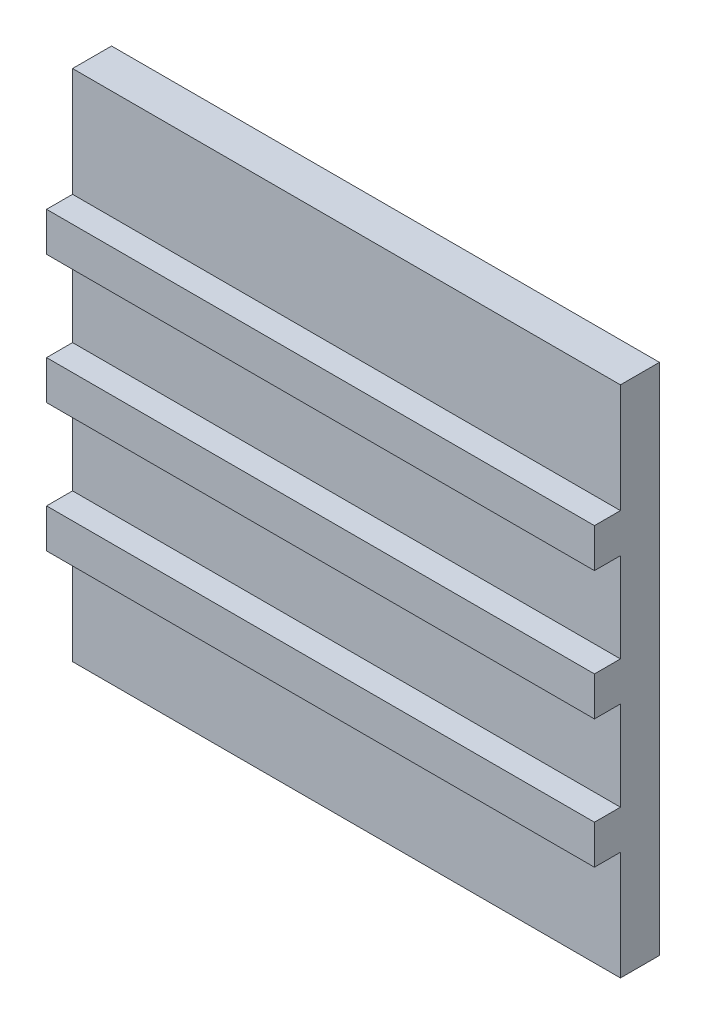
SolidWorks part; units mm, degrees
ref_plane "Front Plane" through (0, 0, 0) normal (0, 0, 1) x (1, 0, 0)
ref_plane "Top Plane" through (0, 0, 0) normal (0, 1, 0) x (1, 0, 0)
ref_plane "Right Plane" through (0, 0, 0) normal (1, 0, 0) x (0, 0, -1)
sketch "Sketch2" plane through (0, 0, 0) normal (0, 0, 1) x (1, 0, 0)
  line L1 (-51.6665, 20.5898) -> (-9.5165, 20.5898)
  line L2 (-51.6665, 20.5898) -> (-51.6665, -18.9302)
  line L3 (-51.6665, -18.9302) -> (-9.5165, -18.9302)
  line L4 (-9.5165, 20.5898) -> (-9.5165, -18.9302)
extrude "Boss-Extrude1" add sketch "Sketch2" along normal blind 3
sketch "Sketch3" plane through (0, 0, 3) normal (0, 0, 1) x (1, 0, 0)
  line L0 (-51.6665, -9.0502) -> (-51.6665, 0.8298) construction
  line L1 (-51.6665, -18.9302) -> (-51.6665, -9.0502) construction
  line L2 (-51.6665, -9.0502) -> (-9.5165, -9.0502) construction
  line L3 (-9.5165, -18.9302) -> (-9.5165, 20.5898) construction
  line L4 (-51.6665, 20.5898) -> (-51.6665, -18.9302) construction
  line L5 (-51.6665, 0.8298) -> (-51.6665, 10.7098) construction
  line L6 (-51.6665, 10.7098) -> (-9.5165, 10.7098) construction
  line L7 (-51.6665, -9.0502) -> (-51.6665, -10.5502)
  line L8 (-51.6665, -9.0502) -> (-51.6665, -7.5502)
  line L9 (-51.6665, -7.5502) -> (-9.5165, -7.5502)
  line L10 (-9.5165, -7.5502) -> (-9.5165, -10.5502)
  line L11 (-9.5165, -10.5502) -> (-51.6665, -10.5502)
  line L12 (-51.6665, 10.7098) -> (-51.6665, 12.2098)
  line L13 (-51.6665, 12.2098) -> (-9.5165, 12.2098)
  line L14 (-9.5165, 12.2098) -> (-9.5165, 9.2098)
  line L15 (-9.5165, 9.2098) -> (-51.6665, 9.2098)
  line L16 (-51.6665, 9.2098) -> (-51.6665, 12.2098)
  line L17 (-51.6665, 0.8298) -> (-9.5165, 0.8298) construction
  line L18 (-51.6665, 0.8298) -> (-51.6665, 2.3298)
  line L19 (-51.6665, 2.3298) -> (-51.6665, -0.6702)
  line L20 (-51.6665, -0.6702) -> (-9.5165, -0.6702)
  line L21 (-9.5165, -0.6702) -> (-9.5165, 2.3298)
  line L22 (-9.5165, 2.3298) -> (-51.6665, 2.3298)
  line M6 (-51.6665, 20.5898) -> (-51.6665, -18.9302)
  line M8 (-9.5165, -18.9302) -> (-9.5165, 20.5898)
extrude "Boss-Extrude2" add sketch "Sketch3" along normal blind 2 contours L15 L13 M8 M6 | L22 L20 M8 M6 | L11 L9 M8 M6
